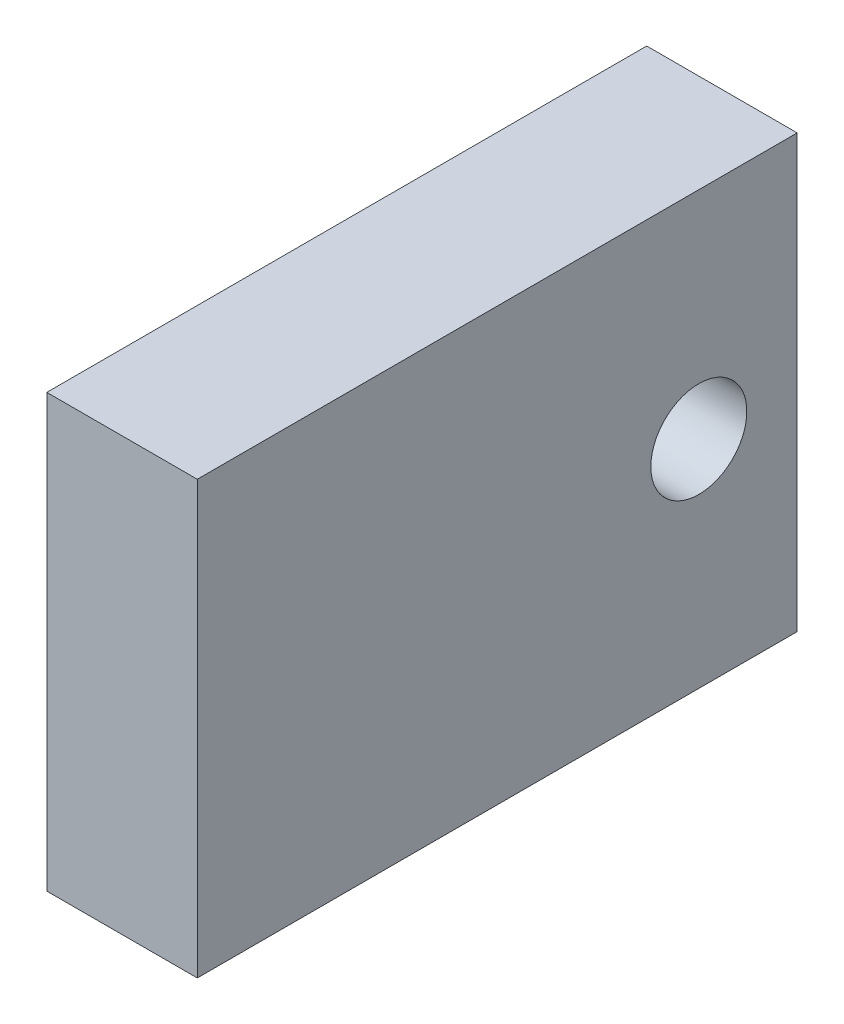
SolidWorks part; units mm, degrees
ref_plane "Front Plane" through (0, 0, 0) normal (0, 0, 1) x (1, 0, 0)
ref_plane "Top Plane" through (0, 0, 0) normal (0, 1, 0) x (1, 0, 0)
ref_plane "Right Plane" through (0, 0, 0) normal (1, 0, 0) x (0, 0, -1)
sketch "Sketch1" plane through (0, 0, 0) normal (0, 1, 0) x (1, 0, 0)
  line L1 (-7.9645, 31.75) -> (7.9645, 31.75)
  line L2 (-7.9645, 31.75) -> (-7.9645, -31.75)
  line L3 (-7.9645, -31.75) -> (7.9645, -31.75)
  line L4 (7.9645, 31.75) -> (7.9645, -31.75)
  line L5 (-7.9645, 31.75) -> (7.9645, -31.75) construction
  line L6 (-7.9645, -31.75) -> (7.9645, 31.75) construction
  point P4 (0, 0)
  point P5 (0, 0)
  dimension "D1" = 63.5
  dimension "D2" = 15.929
extrude "Boss-Extrude1" add sketch "Sketch1" along normal blind 45.72
sketch "Sketch2" plane through (-7.9645, 0, 0) normal (-1, 0, 0) x (0, 0, 1)
  line L0 (-31.75, 45.72) -> (-31.75, 0) construction
  circle A0 centre (-21.336, 22.86) radius 5.08
  point P4 (0, 0)
  point P5 (-31.75, 22.86)
  dimension "D3" = 10.16
  dimension "D1" = 10.414
extrude "Cut-Extrude1" cut sketch "Sketch2" against normal blind 50.8
